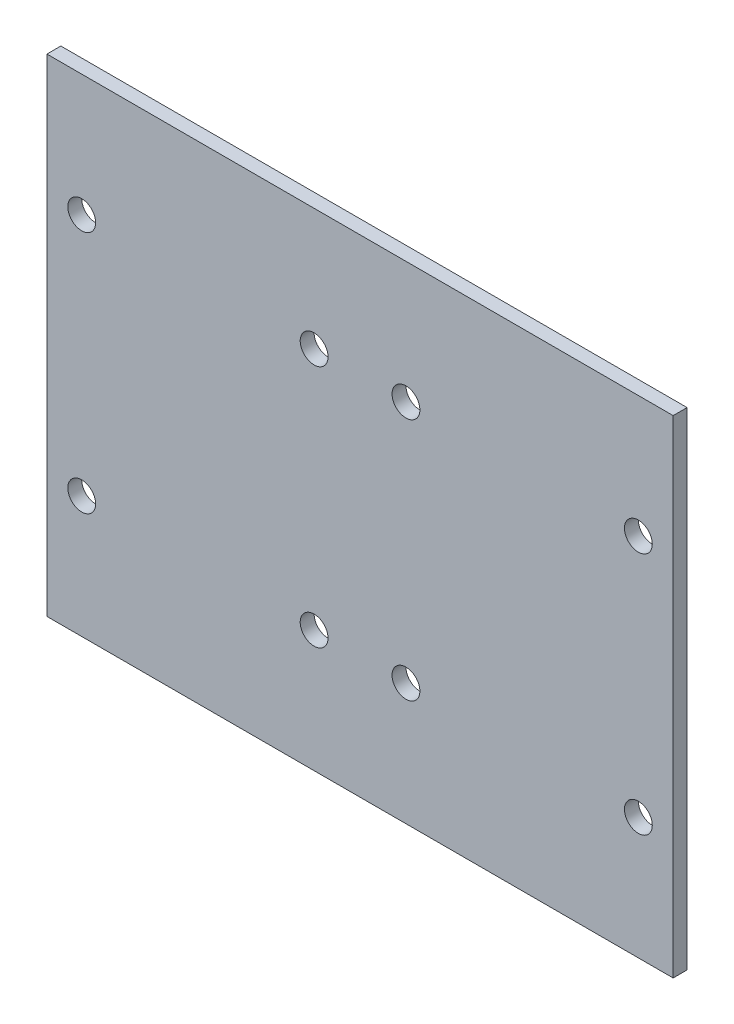
SolidWorks part; units mm, degrees
ref_plane "Front Plane" through (0, 0, 0) normal (0, 0, 1) x (1, 0, 0)
ref_plane "Top Plane" through (0, 0, 0) normal (0, 1, 0) x (1, 0, 0)
ref_plane "Right Plane" through (0, 0, 0) normal (1, 0, 0) x (0, 0, -1)
sketch "Sketch1" plane through (0, 0, 0) normal (0, 0, 1) x (1, 0, 0)
  line L4 (-67.538, 0) -> (61.6563, 0) construction
  line L5 (0, 31.0047) -> (0, -34.6671) construction
  line L6 (-45, 35) -> (-45, -35)
  line L7 (-45, -35) -> (45, -35)
  line L8 (45, -35) -> (45, 35)
  line L9 (45, 35) -> (-45, 35)
  circle A0 centre (-6.6, 17.5) radius 2
  circle A2 centre (6.6, 17.5) radius 2
  circle A3 centre (-6.6, -17.5) radius 2
  circle A4 centre (-40, 17.5) radius 2
  circle A5 centre (-40, -17.5) radius 2
  circle A6 centre (40, 17.5) radius 2
  circle A8 centre (6.6, -17.5) radius 2
  circle A9 centre (40, -17.5) radius 2
  dimension "D1" = 4
  dimension "D2" = 4
  dimension "D3" = 4
  dimension "D4" = 4
  dimension "D5" = 4
  dimension "D6" = 4
  dimension "D7" = 4
  dimension "D10" = 4
  dimension "D8" = 17.5
  dimension "D9" = 33.4
  dimension "D11" = 17.5
  dimension "D12" = 33.4
  dimension "D13" = 33.4
  dimension "D14" = 6.6
  dimension "D15" = 6.6
  dimension "D16" = 33.4
  dimension "D17" = 35
  dimension "D18" = 70
  dimension "D19" = 90
  dimension "D20" = 45
  dimension "D21" = 35
extrude "Boss-Extrude1" add sketch "Sketch1" along normal blind 2
